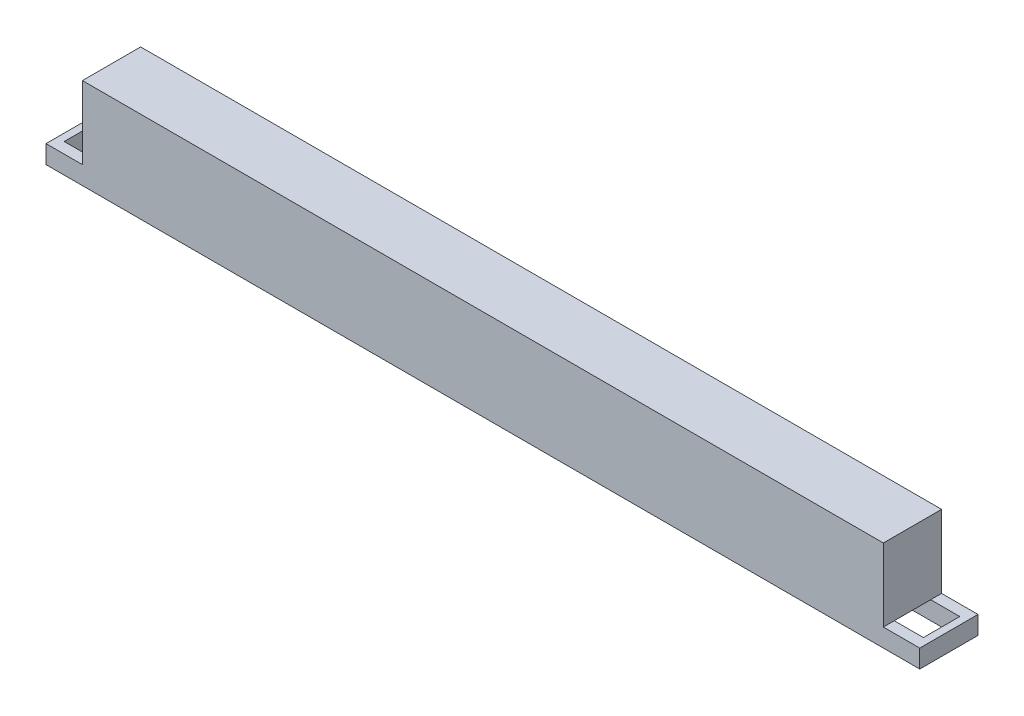
SolidWorks part; units mm, degrees
ref_plane "Front Plane" through (0, 0, 0) normal (0, 0, 1) x (1, 0, 0)
ref_plane "Top Plane" through (0, 0, 0) normal (0, 1, 0) x (1, 0, 0)
ref_plane "Right Plane" through (0, 0, 0) normal (1, 0, 0) x (0, 0, -1)
sketch "Sketch1" plane through (0, 0, 0) normal (0, 1, 0) x (1, 0, 0)
  line L1 (120, -8) -> (-120, -8)
  line L2 (120, -8) -> (120, 8)
  line L3 (120, 8) -> (-120, 8)
  line L4 (-120, -8) -> (-120, 8)
  line L5 (120, -8) -> (-120, 8) construction
  line L6 (120, 8) -> (-120, -8) construction
  point P0 (0, 0)
  dimension "D1" = 240
  dimension "D2" = 16
extrude "Boss-Extrude1" add sketch "Sketch1" along normal blind 5
sketch "Sketch2" plane through (0, 0, 0) normal (0, 1, 0) x (1, 0, 0)
  line L1 (118, -5) -> (-118, -5)
  line L2 (118, -5) -> (118, 5)
  line L3 (118, 5) -> (-118, 5)
  line L4 (-118, -5) -> (-118, 5)
  line L5 (118, -5) -> (-118, 5) construction
  line L6 (118, 5) -> (-118, -5) construction
  point P0 (0, 0)
  dimension "D1" = 236
  dimension "D2" = 10
extrude "Cut-Extrude1" cut sketch "Sketch2" along normal blind 5
ref_plane "Plane1" through (0, 5, 0) normal (0, 1, 0) x (1, 0, 0)
ref_plane "Plane2" through (0, 0, 0) normal (0, -1, 0) x (-1, 0, 0)
ref_plane "Plane3" through (0, 0, 0) normal (0, -1, 0) x (-1, 0, 0)
ref_plane "Plane4" through (0, 5, 0) normal (0, 1, 0) x (1, 0, 0)
sketch "Sketch4" plane through (0, 5, 0) normal (0, 1, 0) x (1, 0, 0)
  line L0 (120, 8) -> (-120, 8) construction
  line L1 (110, -8) -> (-110, -8)
  line L2 (110, -8) -> (110, 8)
  line L3 (110, 8) -> (-110, 8)
  line L4 (-110, -8) -> (-110, 8)
  line L5 (110, -8) -> (-110, 8) construction
  line L6 (110, 8) -> (-110, -8) construction
  line L7 (-120, 8) -> (-120, -8) construction
  point P0 (0, 0)
  dimension "D1" = 10
extrude "Boss-Extrude3" add sketch "Sketch4" along normal blind 20
